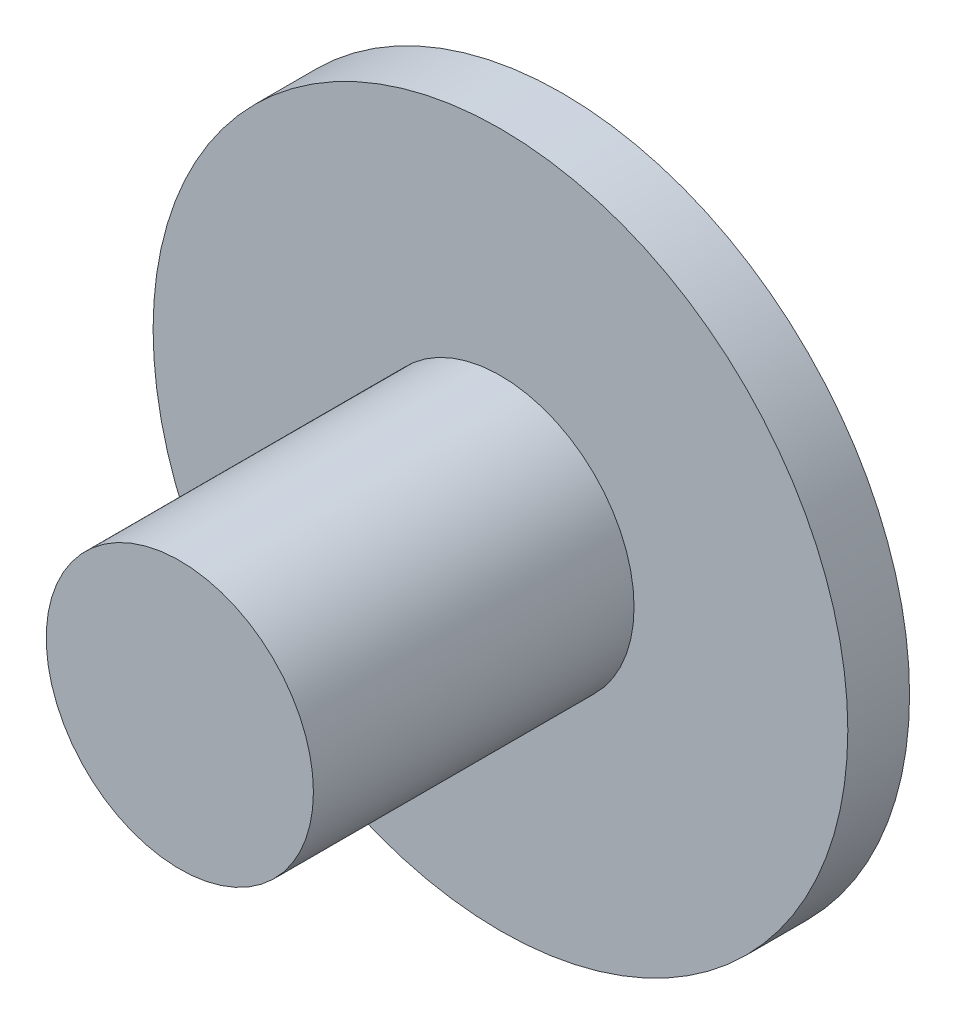
SolidWorks part; units mm, degrees
ref_plane "Front Plane" through (0, 0, 0) normal (0, 0, 1) x (1, 0, 0)
ref_plane "Top Plane" through (0, 0, 0) normal (0, 1, 0) x (1, 0, 0)
ref_plane "Right Plane" through (0, 0, 0) normal (1, 0, 0) x (0, 0, -1)
sketch "Sketch1" plane through (0, 0, 0) normal (0, 0, 1) x (1, 0, 0)
  circle A0 centre (0, 0) radius 5
  dimension "D1" = 10
extrude "Boss-Extrude1" add sketch "Sketch1" along normal blind 80
cosmetic thread "Cosmetic Thread2" parameters "D1"=220.9065, "D2"=6.619
sketch "Sketch2" plane through (0, 0, 0) normal (0, 1, 0) x (1, 0, 0)
  line L0 (0, -66) -> (0, -68)
  line L1 (0, -68) -> (-5, -68)
  line L2 (-5, 0) -> (-5, -80) construction
  line L3 (-5, -68) -> (-13, -68)
  line L4 (-13, -68) -> (-13, -66)
  line L5 (-13, -66) -> (0, -66)
  line L6 (-5, -80) -> (5, -80) construction
  dimension "D1" = 12
  dimension "D2" = 2
  dimension "D3" = 8
  dimension "D4" = 2
revolve "Revolve1" add sketch "Sketch2" angle 360 about L0
scale "Scale1" scale about centroid uniform scaling yes scale factor 1.9329
sketch "Sketch3" plane through (0, 0, 87.0848) normal (0, 0, -1) x (-1, 0, 0)
  circle A1 centre (0, 0) radius 25.1277
  circle A2 centre (0, 0) radius 25.1277
  dimension "D1" = 0
extrude "Boss-Extrude2" add sketch "Sketch3" along normal blind 0.6
sketch "Sketch4" plane through (0, 0, 0) normal (1, 0, 0) x (0, 0, -1)
  line L0 (-86.4848, -25.1277) -> (-86.4848, 25.1277) construction
  line L2 (-76.7052, 26.6901) -> (-76.7052, 0)
  line L3 (-76.7052, 0) -> (46.7369, 0)
  line L4 (46.7369, 0) -> (46.7369, 27.8839)
  line L5 (46.7369, 27.8839) -> (-76.7052, 26.6901)
  dimension "D1" = 9.7797
revolve "Cut-Revolve1" cut sketch "Sketch4" angle 360 about L3
scale "Scale2" scale about centroid uniform scaling yes scale factor 1.5
